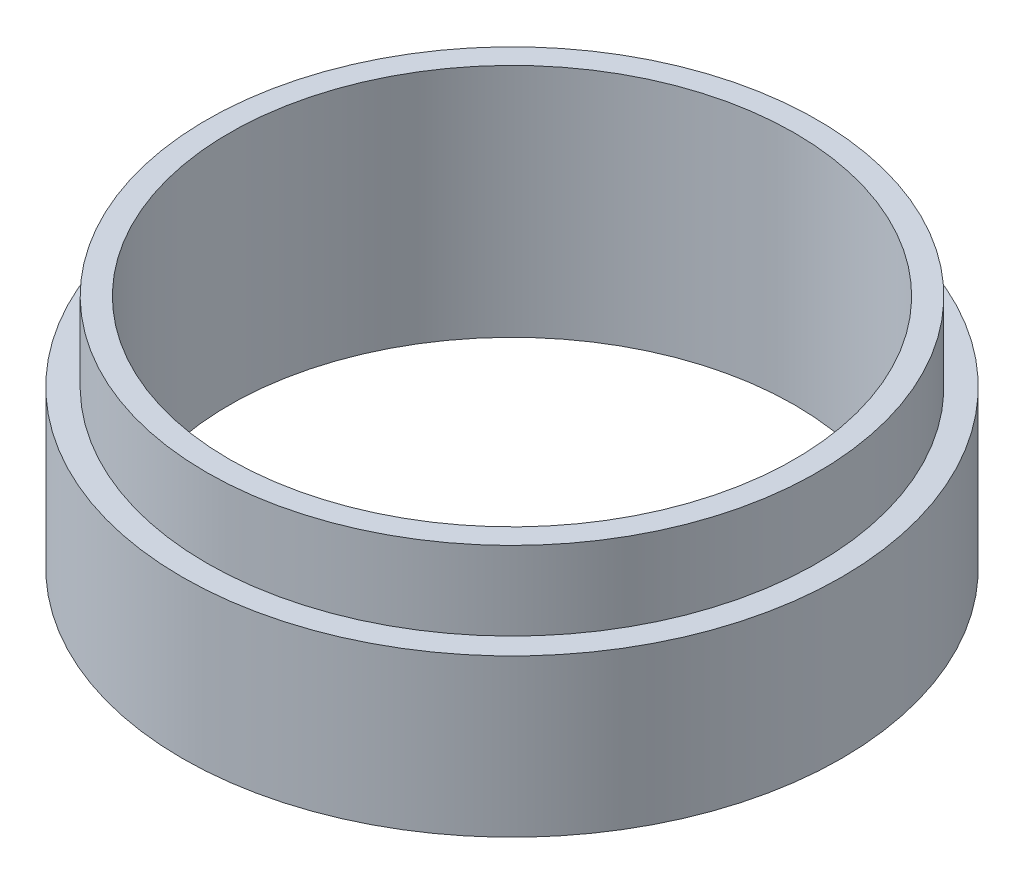
SolidWorks part; units mm, degrees
ref_plane "Front Plane" through (0, 0, 0) normal (0, 0, 1) x (1, 0, 0)
ref_plane "Top Plane" through (0, 0, 0) normal (0, 1, 0) x (1, 0, 0)
ref_plane "Right Plane" through (0, 0, 0) normal (1, 0, 0) x (0, 0, -1)
sketch "Sketch1" plane through (0, 0, 0) normal (0, 0, 1) x (1, 0, 0)
  line L0 (0, 0) -> (0, 23374.4256) construction
  line L1 (0, 0) -> (23374.4256, 0) construction
  line L3 (0, 10) -> (21, 10)
  line L4 (0, 10) -> (0, 0)
  line L5 (0, 0) -> (21, 0)
  line L6 (21, 10) -> (21, 0)
  line L7 (0, 10) -> (21, 0) construction
  line L8 (0, 0) -> (21, 10) construction
  point P5 (10.5, 5)
  dimension "D1" = 42
  dimension "D2" = 10
revolve "Revolve1" add sketch "Sketch1" angle 360 about L0
sketch "Sketch2" plane through (0, 10, 0) normal (0, 1, 0) x (1, 0, 0)
  circle A2 centre (0, 0) radius 18
  circle A3 centre (0, 0) radius 18
  dimension "D1" = 3
extrude "Cut-Extrude1" cut sketch "Sketch2" against normal through all
sketch "Sketch4" plane through (0, 10, 0) normal (0, 1, 0) x (1, 0, 0)
  circle A3 centre (0, 0) radius 19.45
  circle A4 centre (0, 0) radius 19.45
  dimension "D1" = 1.45
extrude "Boss-Extrude1" add sketch "Sketch4" along normal blind 5
sketch "Sketch5" plane through (0, 15, 0) normal (0, 1, 0) x (1, 0, 0)
  circle A2 centre (0, 0) radius 18
  circle A3 centre (0, 0) radius 18
  dimension "D1" = 3
extrude "Cut-Extrude2" cut sketch "Sketch5" against normal through all
